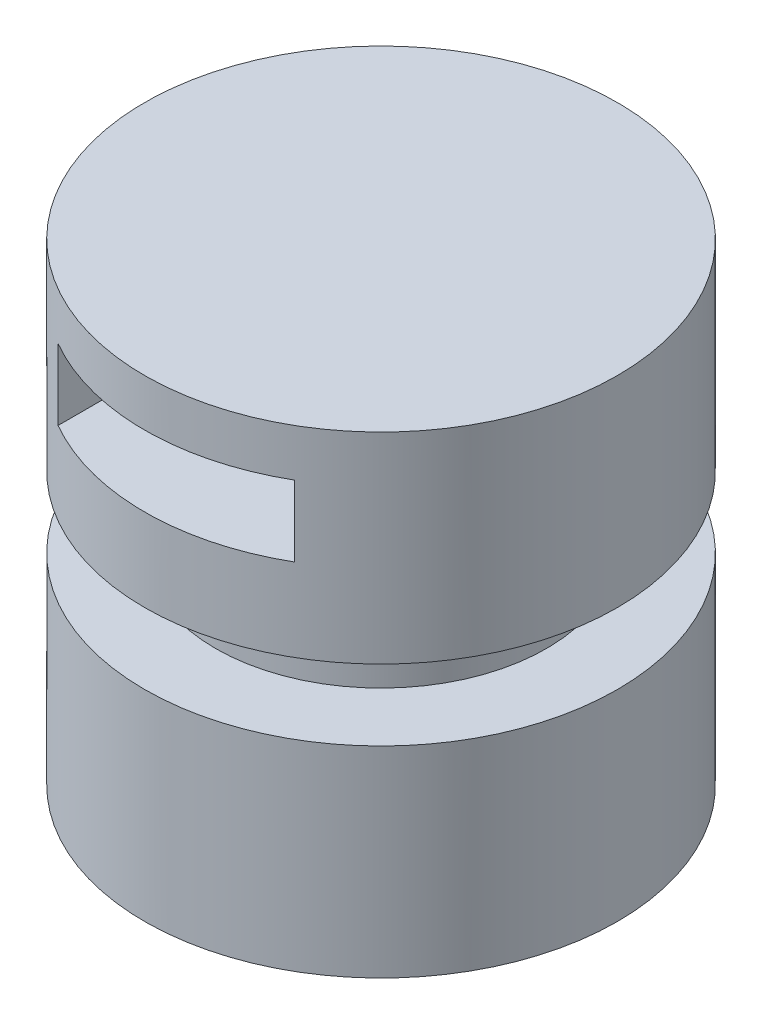
SolidWorks part; units mm, degrees
ref_plane "Front Plane" through (0, 0, 0) normal (0, 0, 1) x (1, 0, 0)
ref_plane "Top Plane" through (0, 0, 0) normal (0, 1, 0) x (1, 0, 0)
ref_plane "Right Plane" through (0, 0, 0) normal (1, 0, 0) x (0, 0, -1)
sketch "Sketch1" plane through (0, 0, 0) normal (0, 0, 1) x (1, 0, 0)
  line L1 (0, 0) -> (2540, 0)
  line L2 (0, 0) -> (0, 5080)
  line L3 (0, 5080) -> (2540, 5080)
  line L4 (2540, 0) -> (2540, 5080)
  dimension "D1" = 2540
  dimension "D2" = 5080
revolve "Revolve1" add sketch "Sketch1" angle 360 about L2
sketch "Sketch2" plane through (0, 0, 0) normal (0, 0, 1) x (1, 0, 0)
  line L0 (-2540, 2540) -> (2540, 2540) construction
  line L1 (-2540, 5080) -> (-2540, 0) construction
  line L2 (2540, 0) -> (2540, 5080) construction
  line L3 (2540, 5080) -> (-2540, 5080) construction
  line L4 (0, 5080) -> (0, 0) construction
  line L5 (1778, 2921) -> (2540, 2921)
  line L6 (1778, 2921) -> (1778, 2159)
  line L7 (1778, 2159) -> (2540, 2159)
  line L8 (2540, 2921) -> (2540, 2159)
  point P12 (1778, 2540)
  dimension "D1" = 762
revolve "Cut-Revolve1" cut sketch "Sketch2" angle 360 about L4
sketch "Sketch3" plane through (0, 0, 0) normal (0, 0, 1) x (1, 0, 0)
  line L0 (2540, 5080) -> (-2540, 5080) construction
  line L1 (-1270, 4572) -> (1270, 4572)
  line L2 (-1270, 4572) -> (-1270, 3810)
  line L3 (-1270, 3810) -> (1270, 3810)
  line L4 (1270, 4572) -> (1270, 3810)
  line L5 (0, 5080) -> (0, 2921) construction
  line L6 (-1778, 2921) -> (1778, 2921) construction
  point P10 (0, 4572)
  dimension "D1" = 762
  dimension "D2" = 2540
  dimension "D3" = 508
extrude "Cut-Extrude1" cut sketch "Sketch3" against normal through all both and the other way through all
